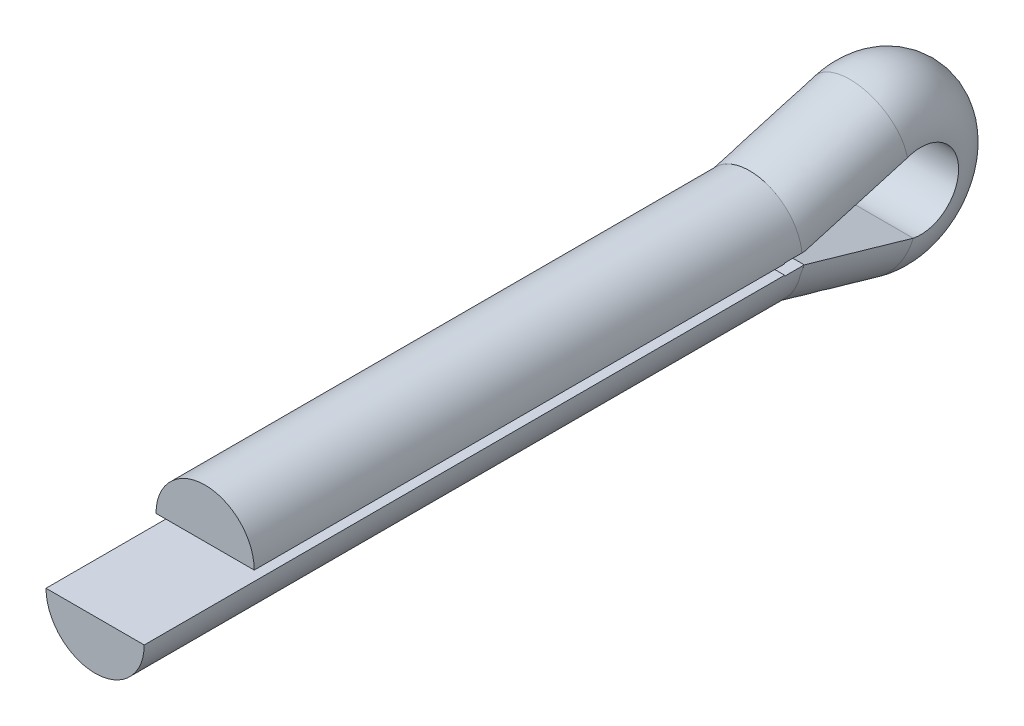
SolidWorks part; units mm, degrees
material "1.7016 (17Cr3)"
ref_plane "Płaszczyzna przednia" through (0, 0, 0) normal (0, 0, 1) x (1, 0, 0)
ref_plane "Płaszczyzna górna" through (0, 0, 0) normal (0, 1, 0) x (1, 0, 0)
ref_plane "Płaszczyzna prawa" through (0, 0, 0) normal (1, 0, 0) x (0, 0, -1)
ref_plane "Płaszczyzna4" through (0, 0, 5) normal (0, 0, 1) x (1, 0, 0)
sketch "Szkic1" plane through (0, 0, 5) normal (0, 0, 1) x (1, 0, 0)
  circle A0 centre (2.5, 0.25) radius 2.5
extrude "Dodanie-wyciągnięcie1" add sketch "Szkic1" along normal blind 0.318
ref_plane "Płaszczyzna1" through (0, 0.25, 0) normal (0, 1, 0) x (1, 0, 0)
sketch "Szkic3" plane through (0, 0, 5) normal (0, 0, 1) x (1, 0, 0)
  circle A0 centre (2.5, -0.25) radius 2.5
extrude "Dodanie-wyciągnięcie2" add sketch "Szkic3" along normal blind 0.318
ref_plane "Płaszczyzna2" through (0, -0.25, 0) normal (0, 1, 0) x (1, 0, 0)
sketch "Szkic8" plane through (0, -0.25, 0) normal (0, 1, 0) x (1, 0, 0)
  line L0 (5, -5.0242) -> (2.5, -5.0242)
  line L1 (2.5, -5.0242) -> (2.5, -5.3423)
  line L2 (2.5, -5.3423) -> (5, -5.3423)
  line L3 (5, -5.3423) -> (5, -5.0242)
  line L4 (2.5, -5.0242) -> (2.5, -5.3423) construction
revolve "Wycięcie-obrót2" cut sketch "Szkic8" angle 360 about L1
sketch "Szkic9" plane through (0, 0, 5.0242) normal (0, 0, 1) x (1, 0, 0)
  circle A0 centre (2.5, 0.25) radius 2.5
extrude "Dodanie-wyciągnięcie3" add sketch "Szkic9" along normal blind 0.318
sketch "Szkic15" plane through (0, 0, 5) normal (0, 0, 1) x (1, 0, 0)
  circle A0 centre (2.5, -0.25) radius 2.5
extrude "Dodanie-wyciągnięcie4" add sketch "Szkic15" along normal blind 0.318
sketch "Szkic21" plane through (0, -0.25, 0) normal (0, 1, 0) x (1, 0, 0)
  line L0 (5, -5.0242) -> (2.5, -5.0242)
  line L1 (2.5, -5.0242) -> (2.5, -5.3423)
  line L2 (2.5, -5.3423) -> (5, -5.3423)
  line L3 (5, -5.3423) -> (5, -5.0242)
  line L4 (2.5, -5.0242) -> (2.5, -5.3423) construction
revolve "Wycięcie-obrót4" cut sketch "Szkic21" angle 360 about L1
sketch "Szkic22" plane through (0, 0, 5.0242) normal (0, 0, 1) x (1, 0, 0)
  circle A0 centre (2.5, 0.25) radius 2.5
extrude "Dodanie-wyciągnięcie5" add sketch "Szkic22" along normal blind 0.318
sketch "Szkic28" plane through (0, 0, 5) normal (0, 0, 1) x (1, 0, 0)
  circle A0 centre (2.5, -0.25) radius 2.5
extrude "Dodanie-wyciągnięcie6" add sketch "Szkic28" along normal blind 0.318
sketch "Szkic34" plane through (0, -0.25, 0) normal (0, 1, 0) x (1, 0, 0)
  line L0 (5, -5.0242) -> (2.5, -5.0242)
  line L1 (2.5, -5.0242) -> (2.5, -5.3423)
  line L2 (2.5, -5.3423) -> (5, -5.3423)
  line L3 (5, -5.3423) -> (5, -5.0242)
  line L4 (2.5, -5.0242) -> (2.5, -5.3423) construction
revolve "Wycięcie-obrót6" cut sketch "Szkic34" angle 360 about L1
sketch "Szkic35" plane through (0, 0, 5) normal (0, 0, 1) x (1, 0, 0)
  line L0 (5, 0.25) -> (0, 0.25)
  arc A0 (0, 0.25) -> (2.5, 2.75) centre (2.5, 0.25) cw
  arc A1 (2.5, 2.75) -> (5, 0.25) centre (2.5, 0.25) cw
extrude "Dodanie-wyciągnięcie7" add sketch "Szkic35" along normal blind 0.318
ref_plane "Płaszczyzna5" through (0, -0.9019, 5.1149) normal (0, -0.1736, 0.9848) x (1, 0, 0)
ref_plane "Płaszczyzna3" through (0, 0, 5.3423) normal (0, 0, 1) x (1, 0, 0)
sketch "Szkic41" plane through (0, 0, 5.3423) normal (0, 0, 1) x (1, 0, 0)
  line L0 (5, 0.25) -> (0, 0.25)
  arc A0 (0, 0.25) -> (5, 0.25) centre (2.5, 0.25) cw
extrude "Dodanie-wyciągnięcie8" add sketch "Szkic41" along normal blind 27.6577
sketch "Szkic42" plane through (0, 0, 5.0242) normal (0, 0, 1) x (1, 0, 0)
  line L0 (0, -0.25) -> (5, -0.25)
  arc A0 (5, -0.25) -> (2.5, -2.75) centre (2.5, -0.25) cw
  arc A1 (2.5, -2.75) -> (0, -0.25) centre (2.5, -0.25) cw
extrude "Dodanie-wyciągnięcie9" add sketch "Szkic42" along normal blind 0.318
sketch "Szkic43" plane through (0, 0, 5.3423) normal (0, 0, 1) x (1, 0, 0)
  line L0 (0, -0.25) -> (5, -0.25)
  arc A0 (5, -0.25) -> (0, -0.25) centre (2.5, -0.25) cw
extrude "Dodanie-wyciągnięcie10" add sketch "Szkic43" along normal blind 33.2577
sketch "Szkic44" plane through (0, 0, 0) normal (1, 0, 0) x (0, 0, -1)
  line L0 (-5.5605, 1.625) -> (0, 3.2263)
  line L2 (-5.5605, -1.63) -> (0, -3.2313)
  line L4 (-33, 0.25) -> (-5.3423, 0.25) construction
  line L5 (-38.6, -0.25) -> (-5.0242, -0.25) construction
  line L6 (-5.5828, 1.7516) -> (-4.647, -3.5554) construction
  arc A0 (0, 3.2263) -> (0, -3.2313) centre (0.9298, -0.0025) cw
  dimension "D1" = 1.375
  dimension "D2" = 1.38
sketch "Szkic45" plane through (0, -0.0236, 5.2698) normal (0, 0.1736, -0.9848) x (-1, 0, 0)
  line L0 (-0.0505, 0.2268) -> (-4.9495, 0.2268) construction
  line L1 (0, 0.2268) -> (-5, 0.2268)
  ellipse E2 centre (-2.5, -0.2698) end of major axis (0, -0.2698) minor radius 2.462 (-4.9875, -0.0236) -> (-0.0125, -0.0236) ccw
  ellipse E3 centre (-2.5, 0.2226) end of major axis (0, 0.2226) minor radius 2.462 (-0.0125, -0.0236) -> (-4.9875, -0.0236) ccw
  ellipse E4 centre (-2.5, 0.2226) end of major axis (0, 0.2226) minor radius 2.462 (0, 0.2268) -> (-5, 0.2268) ccw
  dimension "D1" = 0
sweep "Wyciągnięcie po ścieżce1" add profiles "Szkic45" path "Szkic44"
sketch "Szkic54" plane through (0, 0, 5) normal (0, 0, -1) x (-1, 0, 0)
  line L0 (-4.9997, 0.2888) -> (-0.0003, 0.2888) construction
  line L1 (-5.8316, 0.2888) -> (1.6129, 0.2888)
  line L2 (-5.8316, 0.2888) -> (-5.8316, -0.2938)
  line L3 (-5.8316, -0.2938) -> (1.6129, -0.2938)
  line L4 (1.6129, 0.2888) -> (1.6129, -0.2938)
  line L5 (-5.8316, 0.2888) -> (1.6129, -0.2938) construction
  line L6 (-5.8316, -0.2938) -> (1.6129, 0.2888) construction
  line L7 (-0.0004, -0.2938) -> (-4.9996, -0.2938) construction
  point P0 (-2.1094, -0.0025)
extrude "Wytnij-wyciągnięcie2" cut sketch "Szkic54" against normal blind 1
